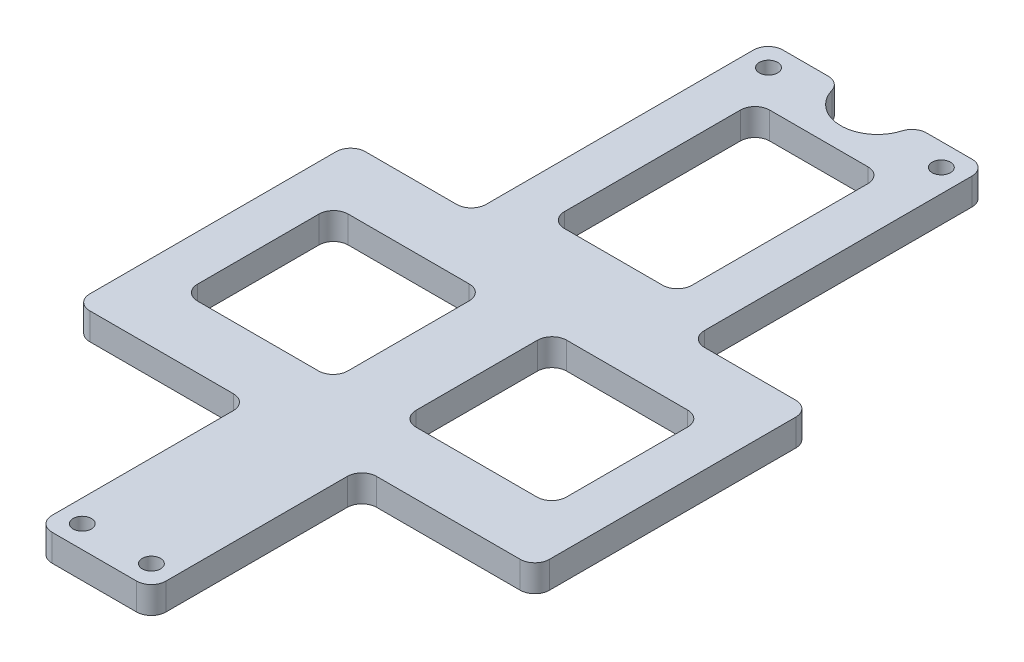
SolidWorks part; units mm, degrees
ref_plane "Front Plane" through (0, 0, 0) normal (0, 0, 1) x (1, 0, 0)
ref_plane "Top Plane" through (0, 0, 0) normal (0, 1, 0) x (1, 0, 0)
ref_plane "Right Plane" through (0, 0, 0) normal (1, 0, 0) x (0, 0, -1)
sketch "Sketch1" plane through (0, 0, 0) normal (0, 1, 0) x (1, 0, 0)
  line L1 (-39.8272, -67.8434) -> (39.8272, -67.8434)
  line L2 (-39.8272, -67.8434) -> (-39.8272, 67.8434)
  line L3 (-39.8272, 67.8434) -> (39.8272, 67.8434)
  line L4 (39.8272, -67.8434) -> (39.8272, 67.8434)
  line L5 (-39.8272, -67.8434) -> (39.8272, 67.8434) construction
  line L6 (-39.8272, 67.8434) -> (39.8272, -67.8434) construction
  point P0 (0, 0)
  dimension "D1" = 79.6544
  dimension "D2" = 135.6868
extrude "Boss-Extrude1" add sketch "Sketch1" along normal blind 4.6482 contours L3 L4 L1 L2
sketch "Sketch2" plane through (0, 4.6482, 0) normal (0, 1, 0) x (1, 0, 0)
  line L0 (39.8272, -67.8434) -> (39.8272, 67.8434) construction
  line L1 (-39.8272, -67.8434) -> (-9.8679, -67.8434)
  line L2 (-39.8272, -67.8434) -> (-39.8272, -31.3436)
  line L3 (-39.8272, -31.3436) -> (-9.8679, -31.3436)
  line L4 (-9.8679, -67.8434) -> (-9.8679, -31.3436)
  line L5 (39.8272, -67.8434) -> (9.8679, -67.8434)
  line L6 (39.8272, -67.8434) -> (39.8272, -31.3436)
  line L7 (39.8272, -31.3436) -> (9.8679, -31.3436)
  line L8 (9.8679, -67.8434) -> (9.8679, -31.3436)
  line L9 (-39.8272, 67.8434) -> (-18.923, 67.8434)
  line L10 (-39.8272, 67.8434) -> (-39.8272, 16.4084)
  line L11 (-39.8272, 16.4084) -> (-18.923, 16.4084)
  line L12 (-18.923, 67.8434) -> (-18.923, 16.4084)
  line L13 (39.8272, 67.8434) -> (18.923, 67.8434)
  line L14 (39.8272, 67.8434) -> (39.8272, 16.4084)
  line L15 (39.8272, 16.4084) -> (18.923, 16.4084)
  line L16 (18.923, 67.8434) -> (18.923, 16.4084)
  line L21 (-31.9532, 5.5626) -> (-5.9055, 5.5626)
  line L22 (-31.9532, 5.5626) -> (-31.9532, -20.5486)
  line L23 (-31.9532, -20.5486) -> (-5.9055, -20.5486)
  line L24 (-5.9055, 5.5626) -> (-5.9055, -20.5486)
  line L25 (5.9055, 5.5626) -> (31.9532, 5.5626)
  line L26 (5.9055, 5.5626) -> (5.9055, -20.5486)
  line L27 (5.9055, -20.5486) -> (31.9532, -20.5486)
  line L28 (31.9532, 5.5626) -> (31.9532, -20.5486)
  line L29 (0, 0) -> (0, -67.8434) construction
  line L30 (-39.8272, -67.8434) -> (39.8272, -67.8434) construction
  line L31 (0, 0) -> (0, 67.8434) construction
  line L32 (-39.8272, 67.8434) -> (39.8272, 67.8434) construction
  line L33 (-39.8272, -67.8434) -> (-39.8272, 67.8434) construction
  line L34 (0, 63.9445) -> (14.9733, 63.9445) construction
  line L35 (-11.049, 22.1234) -> (11.049, 22.1234)
  line L36 (-11.049, 22.1234) -> (-11.049, 57.6834)
  line L37 (-11.049, 57.6834) -> (11.049, 57.6834)
  line L38 (11.049, 22.1234) -> (11.049, 57.6834)
  line L39 (-11.049, 22.1234) -> (11.049, 57.6834) construction
  line L40 (-11.049, 57.6834) -> (11.049, 22.1234) construction
  line L41 (0, 63.9445) -> (-14.9733, 63.9445) construction
  line L42 (0, -63.9445) -> (5.988, -63.9445) construction
  line L43 (0, -63.9445) -> (-5.988, -63.9445) construction
  line L44 (0, 63.9445) -> (0, 67.8434) construction
  line L45 (0, -63.9445) -> (0, -67.8434) construction
  line L46 (0, 57.6834) -> (0, 61.4934) construction
  circle A0 centre (0, 67.8434) radius 6.35
  point P20 (0, 39.9034)
  line M33 (-39.8272, 67.8434) -> (-39.8272, -67.8434)
  line M34 (-39.8272, -67.8434) -> (39.8272, -67.8434)
  line M35 (39.8272, -67.8434) -> (39.8272, 67.8434)
  line M36 (39.8272, 67.8434) -> (-39.8272, 67.8434)
  dimension "D1" = 19.7358
  dimension "D2" = 7.874
  dimension "D3" = 7.874
  dimension "D4" = 11.811
  dimension "D5" = 10.795
  dimension "D7" = 37.846
  dimension "D8" = 22.098
  dimension "D9" = 35.56
  dimension "D10" = 10.16
  dimension "D6" = 47.752
  dimension "D11" = 26.1112
  dimension "D12" = 99.187
  dimension "D13" = 11.9761
  dimension "D14" = 29.9466
  dimension "D15" = 127.889
  dimension "D16" = 3.81
extrude "Cut-Extrude1" cut sketch "Sketch2" against normal through all contours L16 L15 M36 M35 | L35 L38 L37 L36 | L28 L25 L26 L27 | L24 L21 L22 L23 | L4 L3 M34 M33 | L8 L7 M34 M35 | A0 M36 | L12 L11 L10 L9
hole_wizard "1/8 (0.125) Diameter Hole1" positions "3DSketch1" profile "Sketch3" hole size "1/8" standard "ANSI Inch" end condition through all
sketch3d "3DSketch1"
  point P0 (-14.9733, 4.6482, -63.9445)
  point P3 (14.9733, 4.6482, -63.9445)
  point P6 (5.988, 4.6482, 63.9445)
  point P9 (-5.988, 4.6482, 63.9445)
sketch "Sketch3" plane through (-14.9733, 4.6482, -63.9445) normal (1, 0, 0) x (0, 0, 1)
  line L0 (0, 0) -> (0, 4.6482)
  line L1 (0, 4.6482) -> (1.5875, 4.6482)
  line L2 (1.5875, 4.6482) -> (1.5875, 0)
  line L5 (1.5875, 0) -> (0, 0)
  line L11 (0, -6.35) -> (0, 107.95) construction
  dimension "Thru Hole Dia." = 3.175
  dimension "Thru Hole Depth" = 4.6482
fillet "Fillet1" radius 2.54 26 edges at (-9.8679, 2.3241, 31.3436) (-9.8679, 2.3241, 67.8434) (9.8679, 2.3241, 67.8434) (9.8679, 2.3241, 31.3436) (39.8272, 2.3241, 31.3436) (39.8272, 2.3241, -16.4084) (18.923, 2.3241, -16.4084) (18.923, 2.3241, -67.8434) (6.35, 2.3241, -67.8434) (-6.35, 2.3241, -67.8434) (-18.923, 2.3241, -67.8434) (-39.8272, 2.3241, 31.3436) (-39.8272, 2.3241, -16.4084) (-18.923, 2.3241, -16.4084) (-31.9532, 2.3241, -5.5626) (5.9055, 2.3241, -5.5626) (-31.9532, 2.3241, 20.5486) (5.9055, 2.3241, 20.5486) (-5.9055, 2.3241, 20.5486) (31.9532, 2.3241, 20.5486) (-5.9055, 2.3241, -5.5626) (31.9532, 2.3241, -5.5626) (-11.049, 2.3241, -22.1234) (11.049, 2.3241, -22.1234) (11.049, 2.3241, -57.6834) (-11.049, 2.3241, -57.6834)
equation "\"D3@Sketch2\"=\"D2@Sketch2\""
equation "\"D13@Sketch2\"=0.4715"
